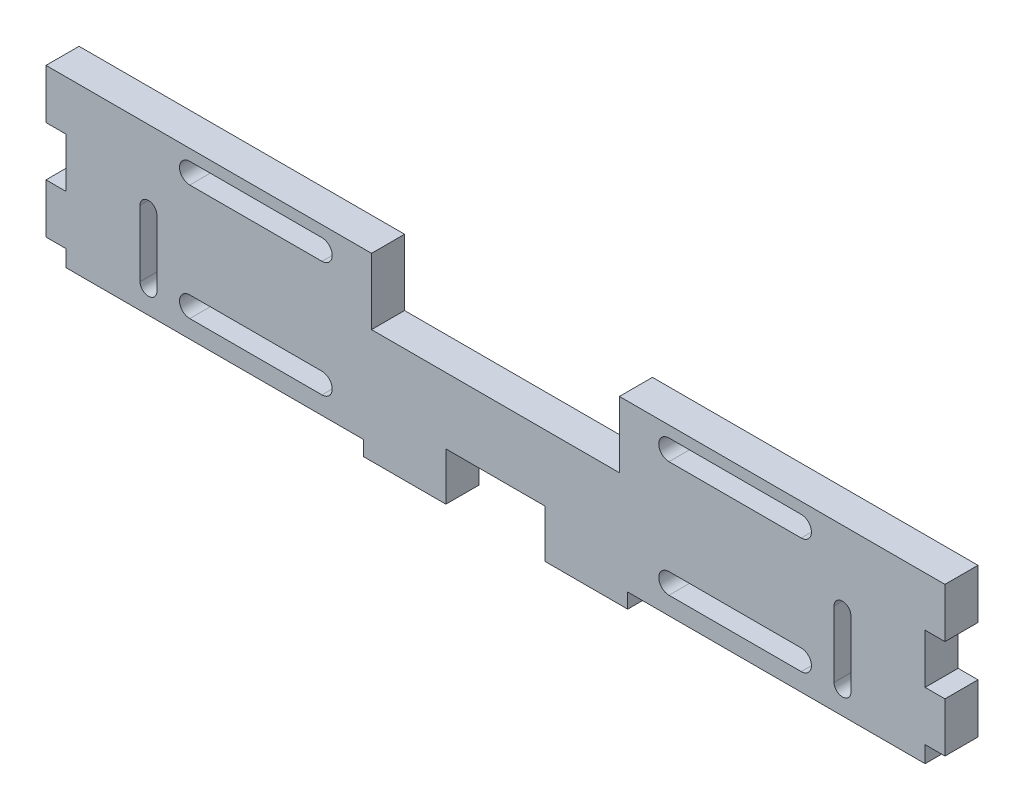
SolidWorks part; units mm, degrees
ref_plane "前基準面" through (0, 0, 0) normal (0, 0, 1) x (1, 0, 0)
ref_plane "上基準面" through (0, 0, 0) normal (0, 1, 0) x (1, 0, 0)
ref_plane "右基準面" through (0, 0, 0) normal (1, 0, 0) x (0, 0, -1)
sketch "草圖1" plane through (0, 0, 0) normal (0, 0, 1) x (1, 0, 0)
  line L0 (136, -22.5) -> (136, -7.5)
  line L1 (136, 22.5) -> (-136, 22.5)
  line L2 (130, 7.5) -> (130, -7.5)
  line L3 (130, -27.5) -> (-130, -27.5)
  line L4 (-130, 7.5) -> (-130, -7.5)
  line L5 (0, -27.5) -> (0, 22.5) construction
  line L6 (130, 0) -> (-130, 0) construction
  line L9 (-130, 7.5) -> (-136, 7.5)
  line L10 (-136, 22.5) -> (-136, 7.5)
  line L14 (-136, -22.5) -> (-136, -7.5)
  line L15 (130, -7.5) -> (136, -7.5)
  line L16 (130, 7.5) -> (136, 7.5)
  line L17 (136, 22.5) -> (136, 7.5)
  line L18 (-136, -22.5) -> (-130, -22.5)
  line L19 (-130, -22.5) -> (-130, -27.5)
  line L20 (-136, -7.5) -> (-130, -7.5)
  line L21 (130, -22.5) -> (130, -27.5)
  line L22 (130, -22.5) -> (136, -22.5)
  point P0 (0, 0)
  point P8 (0, 0)
  point P13 (-136, -15)
  point P14 (136, -15)
  dimension "D1" = 260
  dimension "D2" = 6
  dimension "D3" = 15
  dimension "D4" = 6
  dimension "D5" = 50
  dimension "D6" = 5
extrude "填料-伸長1" add sketch "草圖1" along normal blind 10
sketch "草圖2" plane through (0, 0, 10) normal (0, 0, 1) x (1, 0, 0)
  line L0 (-92.5, 16) -> (-52.5, 16) construction
  line L1 (-92.5, 19.1) -> (-52.5, 19.1)
  line L2 (-92.5, 12.9) -> (-52.5, 12.9)
  line L3 (-92.5, -19) -> (-52.5, -19) construction
  line L4 (-92.5, -15.9) -> (-52.5, -15.9)
  line L5 (-92.5, -22.1) -> (-52.5, -22.1)
  line L6 (0, 61.8937) -> (0, -44.053) construction
  line L7 (-130, -27.5) -> (130, -27.5) construction
  line L8 (52.5, 16) -> (92.5, 16) construction
  line L9 (52.5, 19.1) -> (92.5, 19.1)
  line L10 (52.5, 12.9) -> (92.5, 12.9)
  line L11 (52.5, -19) -> (92.5, -19) construction
  line L12 (52.5, -15.9) -> (92.5, -15.9)
  line L13 (52.5, -22.1) -> (92.5, -22.1)
  arc A0 (-92.5, 19.1) -> (-92.5, 12.9) centre (-92.5, 16) ccw
  arc A1 (-52.5, 12.9) -> (-52.5, 19.1) centre (-52.5, 16) ccw
  arc A2 (-92.5, -15.9) -> (-92.5, -22.1) centre (-92.5, -19) ccw
  arc A3 (-52.5, -22.1) -> (-52.5, -15.9) centre (-52.5, -19) ccw
  arc A4 (52.5, 19.1) -> (52.5, 12.9) centre (52.5, 16) ccw
  arc A5 (92.5, 12.9) -> (92.5, 19.1) centre (92.5, 16) ccw
  arc A6 (52.5, -15.9) -> (52.5, -22.1) centre (52.5, -19) ccw
  arc A7 (92.5, -22.1) -> (92.5, -15.9) centre (92.5, -19) ccw
  point P2 (-72.5, 16)
  point P7 (-72.5, -19)
  point P22 (72.5, 16)
  point P27 (72.5, -19)
  point P37 (-95.6, -19)
  point P38 (49.4, -19)
  dimension "D3" = 3.1
  dimension "D1" = 35
  dimension "D2" = 5.4
  dimension "D4" = 40
  dimension "D6" = 145
  dimension "D5" = 2
extrude "除料-伸長1" cut sketch "草圖2" against normal through all
sketch "草圖3" plane through (0, 0, 10) normal (0, 0, 1) x (1, 0, 0)
  line L0 (0, 40.44) -> (0, -35.44) construction
  line L1 (-130, -27.5) -> (130, -27.5) construction
  line L2 (15, -17.5) -> (-15, -17.5)
  line L3 (15, -17.5) -> (15, -27.5)
  line L4 (15, -27.5) -> (-15, -27.5)
  line L5 (-15, -17.5) -> (-15, -27.5)
  line L6 (0, -27.5) -> (0, -17.5) construction
  line L7 (15, -22.5) -> (-15, -22.5) construction
  line L8 (136, 22.5) -> (-136, 22.5) construction
  line L9 (-37.5, 22.5) -> (37.5, 22.5)
  line L10 (-37.5, 22.5) -> (-37.5, 2.5)
  line L11 (-37.5, 2.5) -> (37.5, 2.5)
  line L12 (37.5, 22.5) -> (37.5, 2.5)
  line L13 (-105, 0.05) -> (-105, -19.95) construction
  line L14 (-102.45, 0.05) -> (-102.45, -19.95)
  line L15 (-107.55, 0.05) -> (-107.55, -19.95)
  line L16 (-130, 7.5) -> (-130, -7.5) construction
  line L17 (105, 0.05) -> (105, -19.95) construction
  line L18 (102.45, 0.05) -> (102.45, -19.95)
  line L19 (107.55, 0.05) -> (107.55, -19.95)
  circle A0 centre (0, 40.44) radius 36 construction
  arc A1 (-102.45, 0.05) -> (-107.55, 0.05) centre (-105, 0.05) ccw
  arc A2 (-107.55, -19.95) -> (-102.45, -19.95) centre (-105, -19.95) ccw
  arc A3 (102.45, 0.05) -> (107.55, 0.05) centre (105, 0.05) cw
  arc A4 (107.55, -19.95) -> (102.45, -19.95) centre (105, -19.95) cw
  point P3 (0, -22.5)
  point P16 (0, 2.5)
  point P22 (-105, -9.95)
  point P29 (-105, -22.5)
  point P30 (0, 0)
  point P33 (105, -9.95)
  dimension "D3" = 72
  dimension "D8" = 5.1
  dimension "D1" = 10
  dimension "D2" = 30
  dimension "D4" = 67.94
  dimension "D5" = 20
  dimension "D6" = 75
  dimension "D7" = 22.45
  dimension "D9" = 5
  dimension "D10" = 20
extrude "除料-伸長2" cut sketch "草圖3" against normal through all
sketch "草圖4" plane through (0, -27.5, 0) normal (0, -1, 0) x (1, 0, 0)
  line L0 (-130, 0) -> (-15, 0) construction
  line L1 (-15, 10) -> (-40, 10)
  line L2 (-15, 10) -> (-15, 0)
  line L3 (-15, 0) -> (-40, 0)
  line L4 (-40, 10) -> (-40, 0)
  line L5 (0, 39.3448) -> (0, -9.8344) construction
  line L6 (15, 0) -> (40, 0)
  line L7 (40, 10) -> (40, 0)
  line L8 (15, 10) -> (40, 10)
  line L9 (15, 10) -> (15, 0)
  dimension "D1" = 25
  dimension "D2" = 30
extrude "填料-伸長2" add sketch "草圖4" along normal blind 4.5
